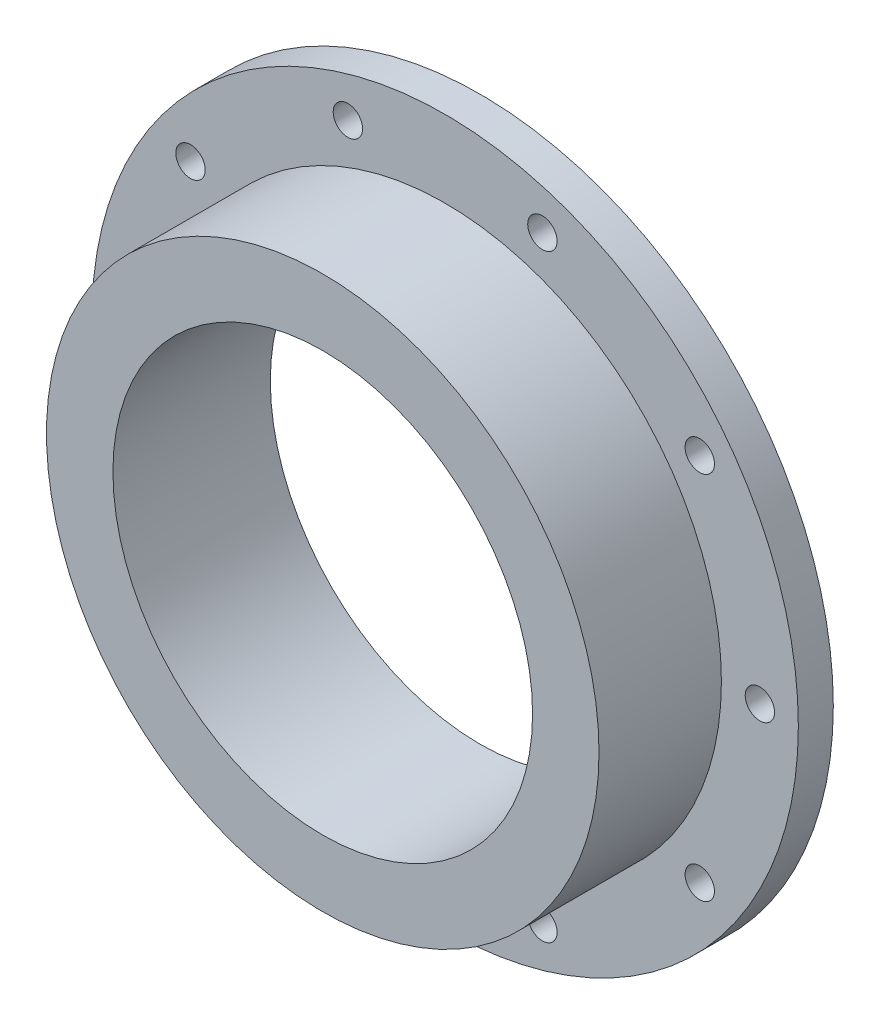
SolidWorks part; units mm, degrees
ref_plane "Front Plane" through (0, 0, 0) normal (0, 0, 1) x (1, 0, 0)
ref_plane "Top Plane" through (0, 0, 0) normal (0, 1, 0) x (1, 0, 0)
ref_plane "Right Plane" through (0, 0, 0) normal (1, 0, 0) x (0, 0, -1)
sketch "Sketch1" plane through (0, 0, 0) normal (0, 1, 0) x (1, 0, 0)
  line L0 (101, 10) -> (0, 10)
  line L1 (0, 10) -> (0, 0)
  line L2 (0, 0) -> (101, 0)
  line L3 (101, 0) -> (101, 10)
  line L4 (0, 10) -> (0, 0) construction
revolve "Revolve1" add sketch "Sketch1" angle 360 about L4
sketch "Sketch2" plane through (0, 0, 0) normal (0, 0, 1) x (1, 0, 0)
  circle A0 centre (0, 0) radius 79
extrude "Boss-Extrude1" add sketch "Sketch2" along normal blind 35
ref_plane "Plane1" through (0, 69.5, 0) normal (0, 1, 0) x (1, 0, 0)
sketch "Sketch3" plane through (0, 69.5, 0) normal (0, 1, 0) x (1, 0, 0)
  line L0 (3.3235, 10) -> (0, 10)
  line L1 (0, 10) -> (0, -5)
  line L2 (0, -5) -> (3.3235, -3.003)
  line L3 (3.3235, -3.003) -> (3.3235, 0)
  line L4 (3.3235, 0) -> (3.3235, 10)
  line L5 (0, 10) -> (0, -5) construction
revolve "Cut-Revolve1" cut sketch "Sketch3" angle 360 about L5
ref_plane "Plane2" through (0, 56.2267, 0) normal (0, 1, 0) x (1, 0, 0)
sketch "Sketch4" plane through (0, 56.2267, 0) normal (0, 1, 0) x (1, 0, 0)
  line L0 (44.1746, 10) -> (40.8511, 10)
  line L1 (40.8511, 10) -> (40.8511, -5)
  line L2 (40.8511, -5) -> (44.1746, -3.003)
  line L3 (44.1746, -3.003) -> (44.1746, 0)
  line L4 (44.1746, 0) -> (44.1746, 10)
  line L5 (40.8511, 10) -> (40.8511, -5) construction
revolve "Cut-Revolve2" cut sketch "Sketch4" angle 360 about L5
ref_plane "Plane3" through (0, 21.4767, 0) normal (0, 1, 0) x (1, 0, 0)
sketch "Sketch5" plane through (0, 21.4767, 0) normal (0, 1, 0) x (1, 0, 0)
  line L0 (69.4219, 10) -> (66.0984, 10)
  line L1 (66.0984, 10) -> (66.0984, -5)
  line L2 (66.0984, -5) -> (69.4219, -3.003)
  line L3 (69.4219, -3.003) -> (69.4219, 0)
  line L4 (69.4219, 0) -> (69.4219, 10)
  line L5 (66.0984, 10) -> (66.0984, -5) construction
revolve "Cut-Revolve3" cut sketch "Sketch5" angle 360 about L5
ref_plane "Plane4" through (0, -21.4767, 0) normal (0, 1, 0) x (1, 0, 0)
sketch "Sketch6" plane through (0, -21.4767, 0) normal (0, 1, 0) x (1, 0, 0)
  line L0 (69.4219, 10) -> (66.0984, 10)
  line L1 (66.0984, 10) -> (66.0984, -5)
  line L2 (66.0984, -5) -> (69.4219, -3.003)
  line L3 (69.4219, -3.003) -> (69.4219, 0)
  line L4 (69.4219, 0) -> (69.4219, 10)
  line L5 (66.0984, 10) -> (66.0984, -5) construction
revolve "Cut-Revolve4" cut sketch "Sketch6" angle 360 about L5
ref_plane "Plane5" through (0, -56.2267, 0) normal (0, 1, 0) x (1, 0, 0)
sketch "Sketch7" plane through (0, -56.2267, 0) normal (0, 1, 0) x (1, 0, 0)
  line L0 (44.1746, 10) -> (40.8511, 10)
  line L1 (40.8511, 10) -> (40.8511, -5)
  line L2 (40.8511, -5) -> (44.1746, -3.003)
  line L3 (44.1746, -3.003) -> (44.1746, 0)
  line L4 (44.1746, 0) -> (44.1746, 10)
  line L5 (40.8511, 10) -> (40.8511, -5) construction
revolve "Cut-Revolve5" cut sketch "Sketch7" angle 360 about L5
ref_plane "Plane6" through (0, -69.5, 0) normal (0, 1, 0) x (1, 0, 0)
sketch "Sketch8" plane through (0, -69.5, 0) normal (0, 1, 0) x (1, 0, 0)
  line L0 (3.3235, 10) -> (0, 10)
  line L1 (0, 10) -> (0, -5)
  line L2 (0, -5) -> (3.3235, -3.003)
  line L3 (3.3235, -3.003) -> (3.3235, 0)
  line L4 (3.3235, 0) -> (3.3235, 10)
  line L5 (0, 10) -> (0, -5) construction
revolve "Cut-Revolve6" cut sketch "Sketch8" angle 360 about L5
sketch "Sketch9" plane through (0, -56.2267, 0) normal (0, 1, 0) x (1, 0, 0)
  line L0 (-37.5276, 10) -> (-40.8511, 10)
  line L1 (-40.8511, 10) -> (-40.8511, -5)
  line L2 (-40.8511, -5) -> (-37.5276, -3.003)
  line L3 (-37.5276, -3.003) -> (-37.5276, 0)
  line L4 (-37.5276, 0) -> (-37.5276, 10)
  line L5 (-40.8511, 10) -> (-40.8511, -5) construction
revolve "Cut-Revolve7" cut sketch "Sketch9" angle 360 about L5
sketch "Sketch10" plane through (0, -21.4767, 0) normal (0, 1, 0) x (1, 0, 0)
  line L0 (-62.7749, 10) -> (-66.0984, 10)
  line L1 (-66.0984, 10) -> (-66.0984, -5)
  line L2 (-66.0984, -5) -> (-62.7749, -3.003)
  line L3 (-62.7749, -3.003) -> (-62.7749, 0)
  line L4 (-62.7749, 0) -> (-62.7749, 10)
  line L5 (-66.0984, 10) -> (-66.0984, -5) construction
revolve "Cut-Revolve8" cut sketch "Sketch10" angle 360 about L5
sketch "Sketch11" plane through (0, 21.4767, 0) normal (0, 1, 0) x (1, 0, 0)
  line L0 (-62.7749, 10) -> (-66.0984, 10)
  line L1 (-66.0984, 10) -> (-66.0984, -5)
  line L2 (-66.0984, -5) -> (-62.7749, -3.003)
  line L3 (-62.7749, -3.003) -> (-62.7749, 0)
  line L4 (-62.7749, 0) -> (-62.7749, 10)
  line L5 (-66.0984, 10) -> (-66.0984, -5) construction
revolve "Cut-Revolve9" cut sketch "Sketch11" angle 360 about L5
sketch "Sketch12" plane through (0, 56.2267, 0) normal (0, 1, 0) x (1, 0, 0)
  line L0 (-37.5276, 10) -> (-40.8511, 10)
  line L1 (-40.8511, 10) -> (-40.8511, -5)
  line L2 (-40.8511, -5) -> (-37.5276, -3.003)
  line L3 (-37.5276, -3.003) -> (-37.5276, 0)
  line L4 (-37.5276, 0) -> (-37.5276, 10)
  line L5 (-40.8511, 10) -> (-40.8511, -5) construction
revolve "Cut-Revolve10" cut sketch "Sketch12" angle 360 about L5
hole_wizard "Ø8.4 (8.4) Diameter Hole1" positions "Sketch14" profile "Sketch13" hole size "Ø8.4" standard "ANSI Metric"
sketch "Sketch14" plane through (0, 0, -10) normal (0, 0, -1) x (-1, 0, 0)
  point P0 (27.8115, 85.5951)
  point P1 (72.8115, 52.9007)
  point P2 (90, 0)
  point P3 (72.8115, -52.9007)
  point P4 (27.8115, -85.5951)
  point P5 (-27.8115, -85.5951)
  point P6 (-72.8115, -52.9007)
  point P7 (-90, 0)
  point P8 (-72.8115, 52.9007)
  point P9 (-27.8115, 85.5951)
sketch "Sketch13" plane through (-27.8115, 85.5951, -10) normal (1, 0, 0) x (0, 1, 0)
  line L0 (0, 0) -> (0, 45)
  line L1 (0, 45) -> (4.2, 45)
  line L2 (4.2, 45) -> (4.2, 0)
  line L5 (4.2, 0) -> (0, 0)
  line L11 (0, -6.35) -> (0, 107.95) construction
  dimension "Thru Hole Dia." = 8.4
  dimension "Thru Hole Depth" = 45
hole_wizard "Hole1" positions "Sketch16" profile "Sketch15" legacy
sketch "Sketch16" plane through (0, 0, -10) normal (0, 0, -1) x (-1, 0, 0)
  point P0 (0, 0)
sketch "Sketch15" plane through (0, 0, -10) normal (1, 0, 0) x (0, 1, 0)
  line L0 (0, 0) -> (0, 45)
  line L1 (0, 45) -> (60, 45)
  line L2 (60, 45) -> (60, 0)
  line L3 (60, 0) -> (0, 0)
  line L4 (0, 110) -> (0, -10) construction
  dimension "Diameter" = 120
  dimension "Depth" = 45
